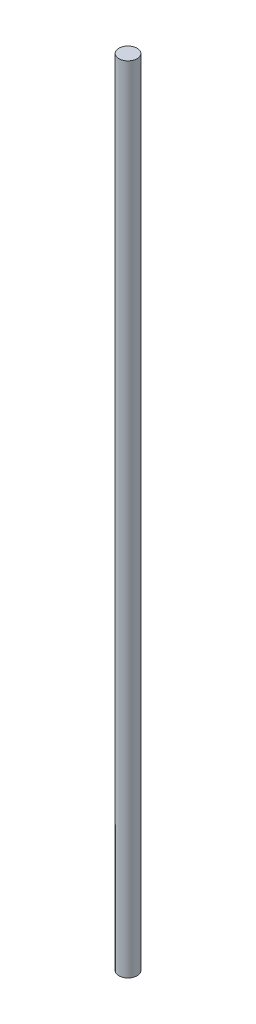
SolidWorks part; units mm, degrees
ref_plane "Front Plane" through (0, 0, 0) normal (0, 0, 1) x (1, 0, 0)
ref_plane "Top Plane" through (0, 0, 0) normal (0, 1, 0) x (1, 0, 0)
ref_plane "Right Plane" through (0, 0, 0) normal (1, 0, 0) x (0, 0, -1)
sketch "Sketch1" plane through (0, 0, 0) normal (0, 1, 0) x (1, 0, 0)
  circle A0 centre (0, 0) radius 6
  dimension "D1" = 12
extrude "Boss-Extrude1" add sketch "Sketch1" along normal blind 523.25
equation "\"d\"= 12"
equation "\"l\"= 523.25"
equation "\"D1@Boss-Extrude1\"= \"l\""
equation "\"D1@Sketch1\"=\"d\""
